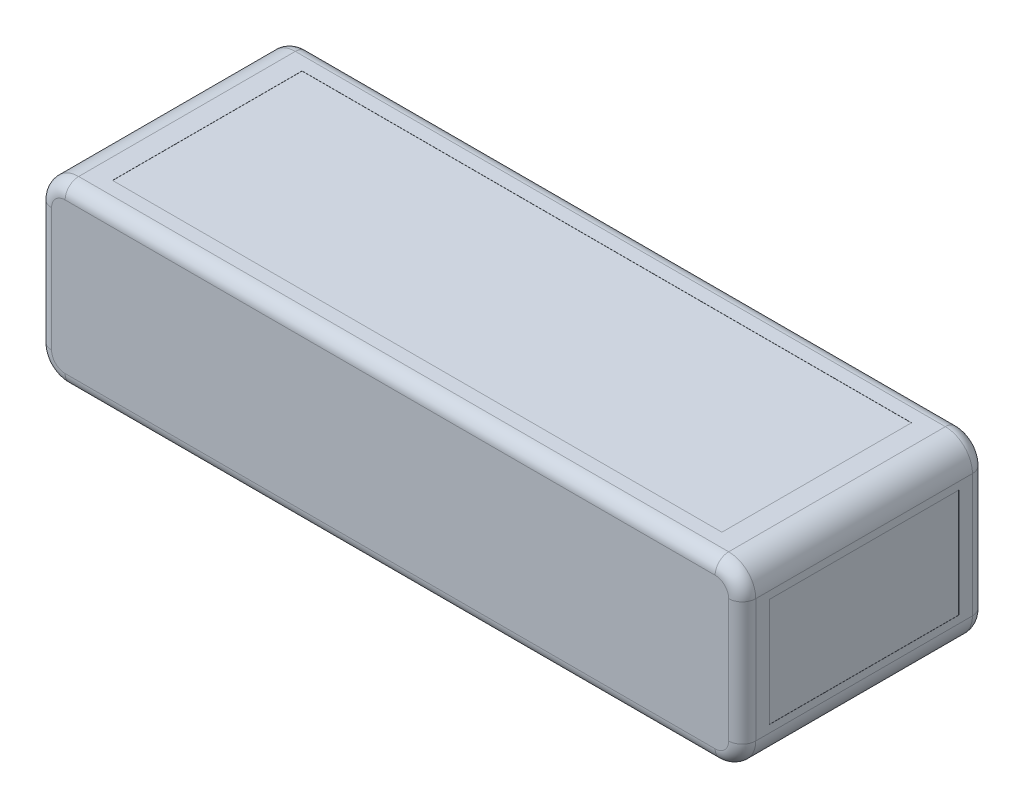
SolidWorks part; units mm, degrees
material "Custom Plastic"
ref_plane "Front Plane" through (0, 0, 0) normal (0, 0, 1) x (1, 0, 0)
ref_plane "Top Plane" through (0, 0, 0) normal (0, 1, 0) x (1, 0, 0)
ref_plane "Right Plane" through (0, 0, 0) normal (1, 0, 0) x (0, 0, -1)
sketch "Sketch1" plane through (0, 0, 0) normal (0, 1, 0) x (1, 0, 0)
  line L1 (-26, -9) -> (26, -9)
  line L2 (-26, -9) -> (-26, 9)
  line L3 (-26, 9) -> (26, 9)
  line L4 (26, -9) -> (26, 9)
  line L5 (-26, -9) -> (26, 9) construction
  line L6 (-26, 9) -> (26, -9) construction
  point P0 (0, 0)
  dimension "D1" = 52
  dimension "D2" = 18
extrude "Boss-Extrude1" add sketch "Sketch1" along normal mid plane 13.1
fillet "Fillet1" radius 2 4 edges at (-26, -6.55, 0) (-26, 6.55, 0) (26, -6.55, 0) (26, 6.55, 0)
fillet "Fillet2" radius 1 16 edges at (-25.4142, 5.9642, 9) (-26, 0, 9) (-25.4142, -5.9642, 9) (0, -6.55, 9) (25.4142, -5.9642, 9) (26, 0, 9) (25.4142, 5.9642, 9) (25.4142, 5.9642, -9) (26, 0, -9) (25.4142, -5.9642, -9) (0, -6.55, -9) (-25.4142, -5.9642, -9) (-26, 0, -9) (-25.4142, 5.9642, -9) (0, 6.55, 9) (0, 6.55, -9)
sketch "Sketch2" plane through (0, 6.55, 0) normal (0, 1, 0) x (1, 0, 0)
  line L1 (-22.5, -7) -> (22.5, -7)
  line L2 (-22.5, -7) -> (-22.5, 7)
  line L3 (-22.5, 7) -> (22.5, 7)
  line L4 (22.5, -7) -> (22.5, 7)
  line L5 (-22.5, -7) -> (22.5, 7) construction
  line L6 (-22.5, 7) -> (22.5, -7) construction
  point P0 (0, 0)
  dimension "D1" = 45
  dimension "D2" = 14
sketch "Sketch3" plane through (-26, 0, 0) normal (-1, 0, 0) x (0, 0, 1)
  line L1 (-7, -4) -> (7, -4)
  line L2 (-7, -4) -> (-7, 4)
  line L3 (-7, 4) -> (7, 4)
  line L4 (7, -4) -> (7, 4)
  line L5 (-7, -4) -> (7, 4) construction
  line L6 (-7, 4) -> (7, -4) construction
  point P0 (0, 0)
  dimension "D1" = 14
  dimension "D2" = 8
extrude "Cut-Extrude1" cut sketch "Sketch2" against normal blind 0.01
extrude "Cut-Extrude2" cut sketch "Sketch3" against normal blind 0.01
mirror "Mirror3" about plane through (0, 0, 0) normal (0, 1, 0) of "Cut-Extrude1"
mirror "Mirror4" about plane through (0, 0, 0) normal (1, 0, 0) of "Cut-Extrude2"
